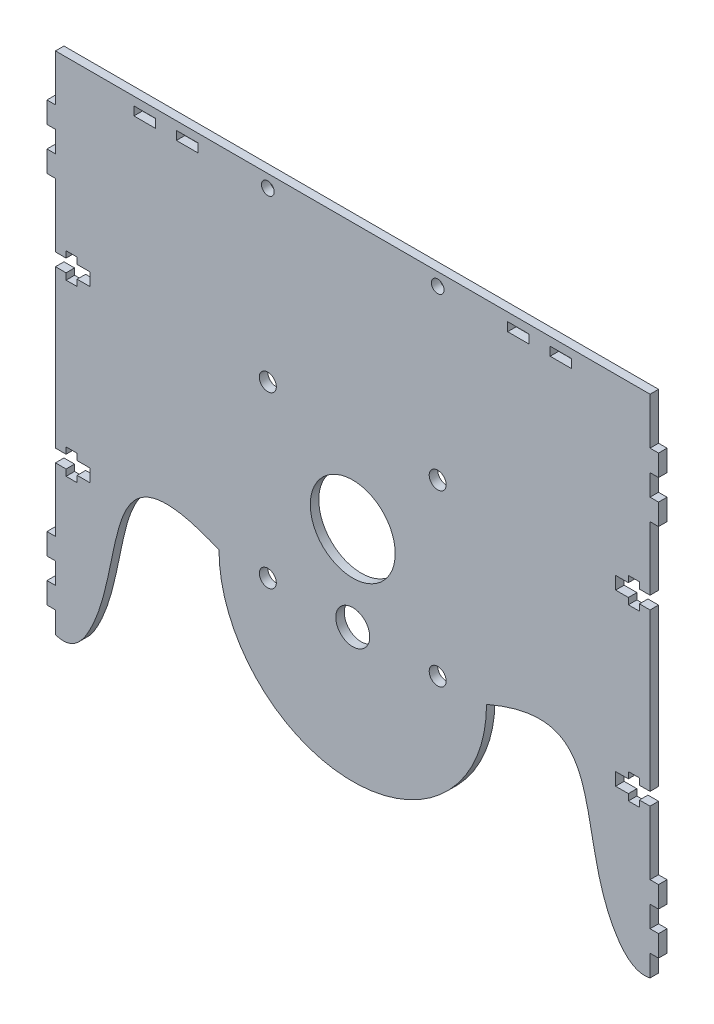
SolidWorks part; units mm, degrees
ref_plane "前视基准面" through (0, 0, 0) normal (0, 0, 1) x (1, 0, 0)
ref_plane "上视基准面" through (0, 0, 0) normal (0, 1, 0) x (1, 0, 0)
ref_plane "右视基准面" through (0, 0, 0) normal (1, 0, 0) x (0, 0, -1)
sketch "草图1" plane through (0, 0, 0) normal (0, 0, 1) x (1, 0, 0)
  line L50 (249.9534, 275.9629) -> (249.9534, 255.9629) construction
  line L53 (317.4534, 257.4629) -> (317.4534, 258.9629)
  line L54 (317.4534, 254.4629) -> (317.4534, 252.9629)
  line L55 (319.9534, 254.4629) -> (317.4534, 254.4629)
  line L56 (317.4534, 258.9629) -> (314.8534, 258.9629)
  line L57 (314.8534, 258.9629) -> (314.8534, 257.4629)
  line L58 (314.8534, 257.4629) -> (311.8534, 257.4629)
  line L59 (311.8534, 254.4629) -> (311.8534, 257.4629)
  line L60 (314.8534, 254.4629) -> (311.8534, 254.4629)
  line L61 (314.8534, 252.9629) -> (314.8534, 254.4629)
  line L62 (317.4534, 252.9629) -> (314.8534, 252.9629)
  line L63 (317.4534, 257.4629) -> (319.9534, 257.4629)
  line L68 (319.9534, 254.4629) -> (319.9534, 257.4629) construction
  line L69 (311.8534, 255.9629) -> (319.9534, 255.9629) construction
  line L73 (311.8534, 295.9629) -> (319.9534, 295.9629) construction
  line L75 (317.4534, 294.4629) -> (319.9534, 294.4629)
  line L76 (317.4534, 298.9629) -> (314.8534, 298.9629)
  line L77 (314.8534, 298.9629) -> (314.8534, 297.4629)
  line L78 (314.8534, 297.4629) -> (311.8534, 297.4629)
  line L79 (311.8534, 297.4629) -> (311.8534, 294.4629)
  line L80 (314.8534, 294.4629) -> (311.8534, 294.4629)
  line L81 (314.8534, 292.9629) -> (314.8534, 294.4629)
  line L82 (317.4534, 292.9629) -> (314.8534, 292.9629)
  line L83 (319.9534, 297.4629) -> (317.4534, 297.4629)
  line L84 (317.4534, 297.4629) -> (317.4534, 298.9629)
  line L85 (317.4534, 294.4629) -> (317.4534, 292.9629)
  line L111 (182.4534, 294.4629) -> (182.4534, 292.9629)
  line L112 (182.4534, 297.4629) -> (182.4534, 298.9629)
  line L113 (179.9534, 297.4629) -> (182.4534, 297.4629)
  line L114 (182.4534, 292.9629) -> (185.0534, 292.9629)
  line L115 (185.0534, 292.9629) -> (185.0534, 294.4629)
  line L116 (185.0534, 294.4629) -> (188.0534, 294.4629)
  line L117 (188.0534, 297.4629) -> (188.0534, 294.4629)
  line L118 (185.0534, 297.4629) -> (188.0534, 297.4629)
  line L119 (185.0534, 298.9629) -> (185.0534, 297.4629)
  line L120 (182.4534, 298.9629) -> (185.0534, 298.9629)
  line L121 (182.4534, 294.4629) -> (179.9534, 294.4629)
  line L122 (182.4534, 257.4629) -> (179.9534, 257.4629)
  line L123 (182.4534, 252.9629) -> (185.0534, 252.9629)
  line L124 (185.0534, 252.9629) -> (185.0534, 254.4629)
  line L125 (185.0534, 254.4629) -> (188.0534, 254.4629)
  line L126 (188.0534, 254.4629) -> (188.0534, 257.4629)
  line L127 (185.0534, 257.4629) -> (188.0534, 257.4629)
  line L128 (185.0534, 258.9629) -> (185.0534, 257.4629)
  line L129 (182.4534, 258.9629) -> (185.0534, 258.9629)
  line L130 (179.9534, 254.4629) -> (182.4534, 254.4629)
  line L131 (182.4534, 254.4629) -> (182.4534, 252.9629)
  line L132 (182.4534, 257.4629) -> (182.4534, 258.9629)
  line L133 (179.9534, 297.4629) -> (179.9534, 294.4629) construction
  line L134 (188.0534, 295.9629) -> (179.9534, 295.9629) construction
  line L135 (188.0534, 255.9629) -> (179.9534, 255.9629) construction
  line L163 (179.9534, 294.4629) -> (179.9534, 257.4629)
  line L172 (319.9534, 257.4629) -> (319.9534, 294.4629)
  line L188 (179.9534, 239.4629) -> (177.9534, 239.4629)
  line L189 (177.9534, 239.4629) -> (177.9534, 234.4629)
  line L190 (177.9534, 234.4629) -> (179.9534, 234.4629)
  line L191 (179.9534, 234.4629) -> (179.9534, 229.4629)
  line L192 (179.9534, 229.4629) -> (177.9534, 229.4629)
  line L193 (177.9534, 229.4629) -> (177.9534, 224.4629)
  line L194 (177.9534, 224.4629) -> (179.9534, 224.4629)
  line L196 (179.9534, 327.4629) -> (179.9534, 345.9629) construction
  line L197 (177.9534, 327.4629) -> (179.9534, 327.4629)
  line L198 (177.9534, 322.4629) -> (177.9534, 327.4629)
  line L199 (179.9534, 322.4629) -> (177.9534, 322.4629)
  line L200 (179.9534, 317.4629) -> (179.9534, 322.4629)
  line L201 (177.9534, 317.4629) -> (179.9534, 317.4629)
  line L202 (177.9534, 312.4629) -> (177.9534, 317.4629)
  line L203 (179.9534, 312.4629) -> (177.9534, 312.4629)
  line L224 (319.9534, 312.4629) -> (321.9534, 312.4629)
  line L225 (321.9534, 312.4629) -> (321.9534, 317.4629)
  line L226 (321.9534, 317.4629) -> (319.9534, 317.4629)
  line L227 (319.9534, 317.4629) -> (319.9534, 322.4629)
  line L228 (319.9534, 322.4629) -> (321.9534, 322.4629)
  line L229 (321.9534, 322.4629) -> (321.9534, 327.4629)
  line L230 (321.9534, 327.4629) -> (319.9534, 327.4629)
  line L231 (319.9534, 327.4629) -> (319.9534, 345.9629) construction
  line L233 (321.9534, 224.4629) -> (319.9534, 224.4629)
  line L234 (321.9534, 229.4629) -> (321.9534, 224.4629)
  line L235 (319.9534, 229.4629) -> (321.9534, 229.4629)
  line L236 (319.9534, 234.4629) -> (319.9534, 229.4629)
  line L237 (321.9534, 234.4629) -> (319.9534, 234.4629)
  line L238 (321.9534, 239.4629) -> (321.9534, 234.4629)
  line L239 (319.9534, 239.4629) -> (321.9534, 239.4629)
  line L261 (249.9534, 255.9629) -> (229.9534, 255.9629) construction
  line L262 (229.9534, 335.4629) -> (269.9534, 335.4629) construction
  line L263 (249.9534, 335.4629) -> (249.9534, 338.4629) construction
  line L268 (179.9534, 297.4629) -> (179.9534, 312.4629)
  line L271 (319.9534, 312.4629) -> (319.9534, 297.4629)
  line L272 (319.9534, 254.4629) -> (319.9534, 239.4629)
  line L275 (179.9534, 239.4629) -> (179.9534, 254.4629)
  line L279 (319.9534, 338.4629) -> (179.9534, 338.4629)
  line L280 (179.9534, 327.4629) -> (179.9534, 338.4629)
  line L285 (319.9534, 338.4629) -> (319.9534, 327.4629)
  line L286 (319.9534, 219.4131) -> (179.9534, 219.4131) construction
  line L287 (319.9534, 219.4131) -> (319.9534, 224.4629)
  line L288 (179.9534, 224.4629) -> (179.9534, 219.4131)
  line L309 (179.9534, 345.9629) -> (319.9534, 345.9629) construction
  line L310 (203.4784, 334.4379) -> (198.4284, 336.4879) construction
  line L311 (286.4284, 336.4879) -> (291.4784, 336.4879)
  line L312 (286.4284, 336.4879) -> (286.4284, 334.4379)
  line L313 (286.4284, 334.4379) -> (291.4784, 334.4379)
  line L314 (291.4784, 336.4879) -> (291.4784, 334.4379)
  line L315 (286.4284, 336.4879) -> (291.4784, 334.4379) construction
  line L316 (286.4284, 334.4379) -> (291.4784, 336.4879) construction
  line L317 (296.4284, 336.4879) -> (301.4784, 336.4879)
  line L318 (296.4284, 336.4879) -> (296.4284, 334.4379)
  line L319 (296.4284, 334.4379) -> (301.4784, 334.4379)
  line L320 (301.4784, 336.4879) -> (301.4784, 334.4379)
  line L321 (296.4284, 336.4879) -> (301.4784, 334.4379) construction
  line L322 (296.4284, 334.4379) -> (301.4784, 336.4879) construction
  line L323 (268.4534, 343.4629) -> (266.9534, 343.4629) [skipped]
  line L324 (271.4534, 343.4629) -> (272.9534, 343.4629) [skipped]
  line L325 (271.4534, 345.9629) -> (271.4534, 343.4629) [skipped]
  line L326 (266.9534, 343.4629) -> (266.9534, 340.8629) [skipped]
  line L327 (266.9534, 340.8629) -> (268.4534, 340.8629) [skipped]
  line L328 (268.4534, 340.8629) -> (268.4534, 337.8629) [skipped]
  line L329 (271.4534, 340.8629) -> (271.4534, 337.8629) [skipped]
  line L330 (272.9534, 340.8629) -> (271.4534, 340.8629) [skipped]
  line L331 (272.9534, 343.4629) -> (272.9534, 340.8629) [skipped]
  line L332 (268.4534, 343.4629) -> (268.4534, 345.9629) [skipped]
  line L333 (231.4534, 343.4629) -> (231.4534, 345.9629) [skipped]
  line L334 (226.9534, 343.4629) -> (226.9534, 340.8629) [skipped]
  line L335 (226.9534, 340.8629) -> (228.4534, 340.8629) [skipped]
  line L336 (228.4534, 340.8629) -> (228.4534, 337.8629) [skipped]
  line L337 (231.4534, 340.8629) -> (231.4534, 337.8629) [skipped]
  line L338 (232.9534, 340.8629) -> (231.4534, 340.8629) [skipped]
  line L339 (232.9534, 343.4629) -> (232.9534, 340.8629) [skipped]
  line L340 (228.4534, 345.9629) -> (228.4534, 343.4629) [skipped]
  line L341 (228.4534, 343.4629) -> (226.9534, 343.4629) [skipped]
  line L342 (231.4534, 343.4629) -> (232.9534, 343.4629) [skipped]
  line L343 (268.4534, 345.9629) -> (231.4534, 345.9629) [skipped]
  line L344 (213.4534, 345.9629) -> (213.4534, 347.9629) [skipped]
  line L345 (213.4534, 347.9629) -> (208.4534, 347.9629) [skipped]
  line L346 (208.4534, 347.9629) -> (208.4534, 345.9629) [skipped]
  line L347 (208.4534, 345.9629) -> (203.4534, 345.9629) [skipped]
  line L348 (203.4534, 345.9629) -> (203.4534, 347.9629) [skipped]
  line L349 (203.4534, 347.9629) -> (198.4534, 347.9629) [skipped]
  line L350 (198.4534, 347.9629) -> (198.4534, 345.9629) [skipped]
  line L352 (301.4534, 345.9629) -> (319.9534, 345.9629) [skipped]
  line L353 (301.4534, 347.9629) -> (301.4534, 345.9629) [skipped]
  line L354 (296.4534, 347.9629) -> (301.4534, 347.9629) [skipped]
  line L355 (296.4534, 345.9629) -> (296.4534, 347.9629) [skipped]
  line L356 (291.4534, 345.9629) -> (296.4534, 345.9629) [skipped]
  line L357 (291.4534, 347.9629) -> (291.4534, 345.9629) [skipped]
  line L358 (286.4534, 347.9629) -> (291.4534, 347.9629) [skipped]
  line L359 (286.4534, 345.9629) -> (286.4534, 347.9629) [skipped]
  line L360 (271.4534, 345.9629) -> (268.4534, 345.9629) construction
  line L361 (269.9534, 337.8629) -> (269.9534, 345.9629) construction
  line L362 (229.9534, 337.8629) -> (229.9534, 345.9629) construction
  line L363 (271.4534, 337.8629) -> (268.4534, 337.8629) [skipped]
  line L364 (228.4534, 337.8629) -> (231.4534, 337.8629) [skipped]
  line L365 (203.4784, 336.4879) -> (198.4284, 334.4379) construction
  line L366 (213.4784, 334.4379) -> (208.4284, 336.4879) construction
  line L367 (213.4784, 336.4879) -> (208.4284, 334.4379) construction
  line L368 (198.4284, 336.4879) -> (198.4284, 334.4379)
  line L369 (203.4784, 334.4379) -> (198.4284, 334.4379)
  line L370 (203.4784, 336.4879) -> (203.4784, 334.4379)
  line L371 (203.4784, 336.4879) -> (198.4284, 336.4879)
  line L372 (208.4284, 336.4879) -> (208.4284, 334.4379)
  line L373 (213.4784, 334.4379) -> (208.4284, 334.4379)
  line L374 (213.4784, 336.4879) -> (213.4784, 334.4379)
  line L375 (213.4784, 336.4879) -> (208.4284, 336.4879)
  line L376 (231.4534, 208.4629) -> (232.9534, 208.4629) [skipped]
  line L377 (228.4534, 208.4629) -> (226.9534, 208.4629) [skipped]
  line L378 (228.4534, 205.9629) -> (228.4534, 208.4629) [skipped]
  line L379 (232.9534, 208.4629) -> (232.9534, 211.0629) [skipped]
  line L380 (232.9534, 211.0629) -> (231.4534, 211.0629) [skipped]
  line L381 (231.4534, 211.0629) -> (231.4534, 214.0629) [skipped]
  line L382 (228.4534, 214.0629) -> (231.4534, 214.0629) [skipped]
  line L383 (228.4534, 211.0629) -> (228.4534, 214.0629) [skipped]
  line L384 (226.9534, 211.0629) -> (228.4534, 211.0629) [skipped]
  line L385 (226.9534, 208.4629) -> (226.9534, 211.0629) [skipped]
  line L386 (231.4534, 208.4629) -> (231.4534, 205.9629) [skipped]
  line L387 (268.4534, 208.4629) -> (268.4534, 205.9629) [skipped]
  line L388 (272.9534, 208.4629) -> (272.9534, 211.0629) [skipped]
  line L389 (272.9534, 211.0629) -> (271.4534, 211.0629) [skipped]
  line L390 (271.4534, 211.0629) -> (271.4534, 214.0629) [skipped]
  line L391 (271.4534, 214.0629) -> (268.4534, 214.0629) [skipped]
  line L392 (268.4534, 211.0629) -> (268.4534, 214.0629) [skipped]
  line L393 (266.9534, 211.0629) -> (268.4534, 211.0629) [skipped]
  line L394 (266.9534, 208.4629) -> (266.9534, 211.0629) [skipped]
  line L395 (271.4534, 205.9629) -> (271.4534, 208.4629) [skipped]
  line L396 (271.4534, 208.4629) -> (272.9534, 208.4629) [skipped]
  line L397 (268.4534, 208.4629) -> (266.9534, 208.4629) [skipped]
  line L398 (231.4534, 205.9629) -> (268.4534, 205.9629) [skipped]
  line L399 (286.4534, 205.9629) -> (286.4534, 203.9629) [skipped]
  line L400 (286.4534, 203.9629) -> (291.4534, 203.9629) [skipped]
  line L401 (291.4534, 203.9629) -> (291.4534, 205.9629) [skipped]
  line L402 (291.4534, 205.9629) -> (296.4534, 205.9629) [skipped]
  line L403 (296.4534, 205.9629) -> (296.4534, 203.9629) [skipped]
  line L404 (296.4534, 203.9629) -> (301.4534, 203.9629) [skipped]
  line L405 (198.4534, 205.9629) -> (179.9534, 205.9629) [skipped]
  line L406 (198.4534, 203.9629) -> (198.4534, 205.9629) [skipped]
  line L407 (203.4534, 203.9629) -> (198.4534, 203.9629) [skipped]
  line L408 (203.4534, 205.9629) -> (203.4534, 203.9629) [skipped]
  line L409 (208.4534, 205.9629) -> (203.4534, 205.9629) [skipped]
  line L410 (208.4534, 203.9629) -> (208.4534, 205.9629) [skipped]
  line L411 (213.4534, 203.9629) -> (208.4534, 203.9629) [skipped]
  line L412 (213.4534, 205.9629) -> (213.4534, 203.9629) [skipped]
  line L413 (228.4534, 205.9629) -> (231.4534, 205.9629) construction
  line L414 (229.9534, 214.0629) -> (229.9534, 205.9629) construction
  line L415 (269.9534, 214.0629) -> (269.9534, 205.9629) construction
  line L416 (319.9534, 224.4629) -> (319.9534, 205.9629) [skipped]
  line L417 (301.4534, 203.9629) -> (301.4534, 205.9629) [skipped]
  circle A14 centre (249.9534, 275.9629) radius 10
  circle A24 centre (249.9534, 255.9629) radius 4
  circle A27 centre (229.9534, 335.4629) radius 1.5
  circle A28 centre (269.9534, 335.4629) radius 1.5
  circle A29 centre (229.9534, 255.9629) radius 2
  circle A30 centre (229.9534, 295.9629) radius 2
  circle A31 centre (269.9534, 295.9629) radius 2
  circle A32 centre (269.9534, 255.9629) radius 2
  circle A33 centre (249.9534, 255.9629) radius 31.5 construction
  arc A34 (281.4534, 255.9629) -> (218.4534, 255.9629) centre (249.9534, 255.9629) cw
  spline S0 degree 3 poles (281.4534, 255.9629) (311.1174, 268.7884) (299.9639, 235.828) (316.3683, 218.5927) (319.9534, 219.4131) knots 0 0 0 0 0.841205 1 1 1 1
  spline S1 degree 3 poles (218.4534, 255.9629) (189.4343, 268.3546) (198.5955, 236.6105) (183.8993, 218.0753) (179.9534, 219.4131) knots 0 0 0 0 0.83714 1 1 1 1
  point P107 (210.9534, 335.4629)
  point P232 (288.9534, 335.4629)
  dimension "D1" = 140
  dimension "D5" = 4
  dimension "D4" = 4
extrude "凸台-拉伸1" add sketch "草图1" along normal blind 2
sketch "草图2" plane through (179.9534, 0, 0) normal (-1, 0, 0) x (0, 0, 1)
  line L0 (1, 294.4629) -> (1, 297.4629) construction
  line L1 (2, 294.4629) -> (0, 294.4629) construction
  line L2 (2, 297.4629) -> (0, 297.4629) construction
  line L3 (1, 295.9629) -> (1, 312.4629) construction
  line L4 (2, 312.4629) -> (0, 312.4629) construction
  circle A0 centre (1, 295.9629) radius 1.5
sketch "草图4" plane through (319.9534, 0, 0) normal (1, 0, 0) x (0, 0, -1)
  line L0 (-1, 257.4629) -> (-1, 254.4629) construction
  line L1 (-2, 257.4629) -> (0, 257.4629) construction
  line L2 (-2, 254.4629) -> (0, 254.4629) construction
  circle A0 centre (-1, 255.9629) radius 1.5
sketch "草图6" plane through (0, 0, 2) normal (0, 0, 1) x (1, 0, 0)
  line L0 (317.9092, 345.9629) -> (317.9092, 336.4629)
  line L2 (317.9092, 336.4629) -> (319.9534, 336.4629)
  line L3 (319.9534, 336.4629) -> (319.9534, 345.9629)
  line L4 (319.9534, 345.9629) -> (317.9092, 345.9629)
extrude "切除-拉伸1" [suppressed] cut sketch "草图6" against normal blind 10
